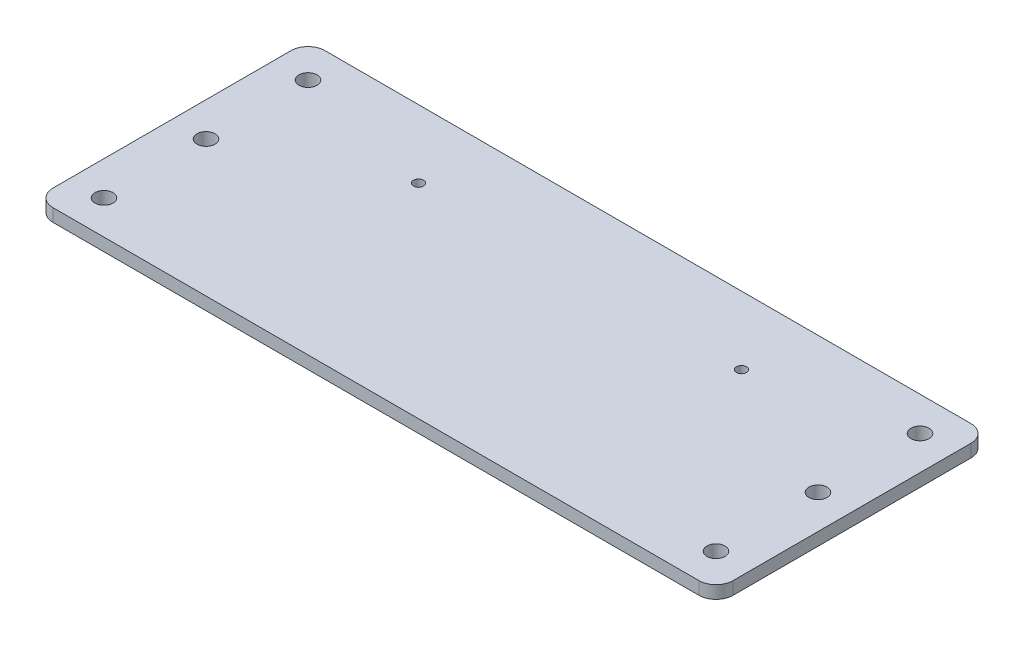
SolidWorks part; units mm, degrees
ref_plane "Front Plane" through (0, 0, 0) normal (0, 0, 1) x (1, 0, 0)
ref_plane "Top Plane" through (0, 0, 0) normal (0, 1, 0) x (1, 0, 0)
ref_plane "Right Plane" through (0, 0, 0) normal (1, 0, 0) x (0, 0, -1)
sketch "Sketch2" plane through (0, 0, 0) normal (0, 1, 0) x (1, 0, 0)
  line L1 (0, 0) -> (254, 0)
  line L2 (0, 0) -> (0, -101.6)
  line L3 (0, -101.6) -> (254, -101.6)
  line L4 (254, 0) -> (254, -101.6)
  point P5 (66.675, -25.4)
  point P6 (187.325, -25.4)
  point P7 (12.7, -88.9)
  point P8 (12.7, -12.7)
  point P9 (241.3, -88.9)
  point P10 (241.3, -12.7)
  point P11 (241.3, -50.8)
  point P15 (12.7, -50.8)
  dimension "D1" = 101.6
  dimension "D2" = 254
  dimension "D3" = 120.65
  dimension "D4" = 66.675
  dimension "D5" = 25.4
  dimension "D6" = 12.7
  dimension "D7" = 12.7
  dimension "D8" = 12.7
  dimension "D9" = 12.7
  dimension "D10" = 38.1
extrude "Boss-Extrude1" add sketch "Sketch2" along normal blind 4.7625
fillet "Fillet1" radius 6.35 4 edges at (254, 2.3813, 0) (254, 2.3813, 101.6) (0, 2.3813, 101.6) (0, 2.3813, 0)
hole_wizard "#6 Clearance Hole1" positions "Sketch3" profile "Sketch4" hole size "#6" standard "ANSI Inch" end condition through all
sketch "Sketch3" plane through (0, 4.7625, 0) normal (0, 1, 0) x (1, 0, 0)
  point P0 (66.675, -25.4)
  point P3 (187.325, -25.4)
sketch "Sketch4" plane through (66.675, 4.7625, 25.4) normal (1, 0, 0) x (0, 0, 1)
  line L0 (0, 0) -> (0, 4.7625)
  line L1 (0, 4.7625) -> (1.8986, 4.7625)
  line L2 (1.8986, 4.7625) -> (1.8986, 0)
  line L5 (1.8986, 0) -> (0, 0)
  line L11 (0, -6.35) -> (0, 107.95) construction
  dimension "Thru Hole Dia." = 3.7973
  dimension "Thru Hole Depth" = 4.7625
hole_wizard "1/4 Clearance Hole1" positions "Sketch5" profile "Sketch6" hole size "1/4" standard "ANSI Inch" end condition through all
sketch "Sketch5" plane through (0, 4.7625, 0) normal (0, 1, 0) x (1, 0, 0)
  point P0 (12.7, -12.7)
  point P3 (12.7, -88.9)
  point P6 (241.3, -88.9)
  point P9 (241.3, -12.7)
  point P13 (12.7, -50.8)
  point P16 (241.3, -50.8)
sketch "Sketch6" plane through (12.7, 4.7625, 12.7) normal (1, 0, 0) x (0, 0, 1)
  line L0 (0, 0) -> (0, 4.7625)
  line L1 (0, 4.7625) -> (3.3782, 4.7625)
  line L2 (3.3782, 4.7625) -> (3.3782, 0)
  line L5 (3.3782, 0) -> (0, 0)
  line L11 (0, -6.35) -> (0, 107.95) construction
  dimension "Thru Hole Dia." = 6.7564
  dimension "Thru Hole Depth" = 4.7625
